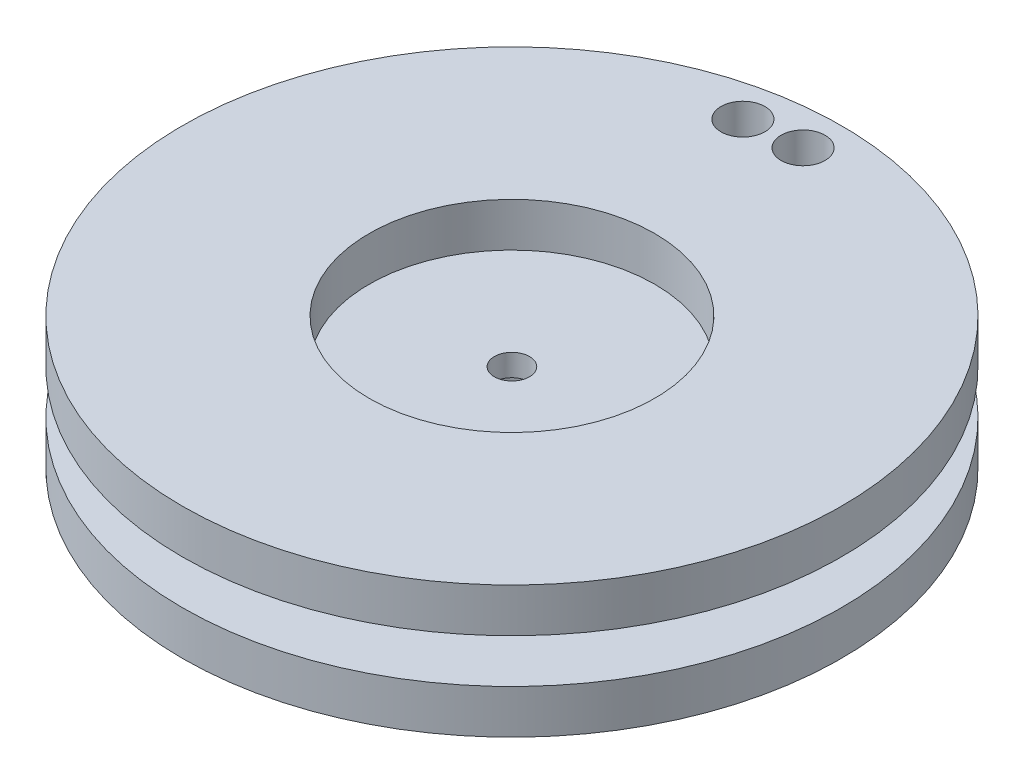
SolidWorks part; units mm, degrees
ref_plane "Front Plane" through (0, 0, 0) normal (0, 0, 1) x (1, 0, 0)
ref_plane "Top Plane" through (0, 0, 0) normal (0, 1, 0) x (1, 0, 0)
ref_plane "Right Plane" through (0, 0, 0) normal (1, 0, 0) x (0, 0, -1)
sketch "Sketch1" plane through (0, 0, 0) normal (0, 1, 0) x (1, 0, 0)
  circle A0 centre (0, 0) radius 15
extrude "Boss-Extrude1" add sketch "Sketch1" along normal blind 2
sketch "Sketch2" plane through (0, 2, 0) normal (0, 1, 0) x (1, 0, 0)
  circle A0 centre (0, 0) radius 12
extrude "Boss-Extrude2" add sketch "Sketch2" along normal blind 2
sketch "Sketch3" plane through (0, 4, 0) normal (0, 1, 0) x (1, 0, 0)
  circle A0 centre (0, 0) radius 15
extrude "Boss-Extrude3" add sketch "Sketch3" along normal blind 2
sketch "Sketch4" plane through (0, 6, 0) normal (0, 1, 0) x (1, 0, 0)
  circle A0 centre (0, 0) radius 6.5
sketch "Sketch6" plane through (0, 0, 0) normal (0, -1, 0) x (1, 0, 0)
  circle A0 centre (0, 0) radius 2.5
extrude "Cut-Extrude5" cut sketch "Sketch6" against normal blind 3
extrude "Cut-Extrude6" cut sketch "Sketch4" against normal blind 2 contours A0
sketch "Sketch10" plane through (0, 4, 0) normal (0, 1, 0) x (1, 0, 0)
  circle A0 centre (0, 0) radius 0.8
extrude "Cut-Extrude7" cut sketch "Sketch10" against normal through all contours A0
sketch "Sketch11" plane through (0, 6, 0) normal (0, 1, 0) x (1, 0, 0)
  circle A0 centre (0, 0) radius 13.25 construction
  circle A1 centre (0, 13.25) radius 1
  circle A2 centre (-2.5, 13.012) radius 1
  dimension "D1" = 26.5
  dimension "D2" = 2
  dimension "D3" = 2
  dimension "D4" = 2.5
extrude "Cut-Extrude8" cut sketch "Sketch11" against normal through all
